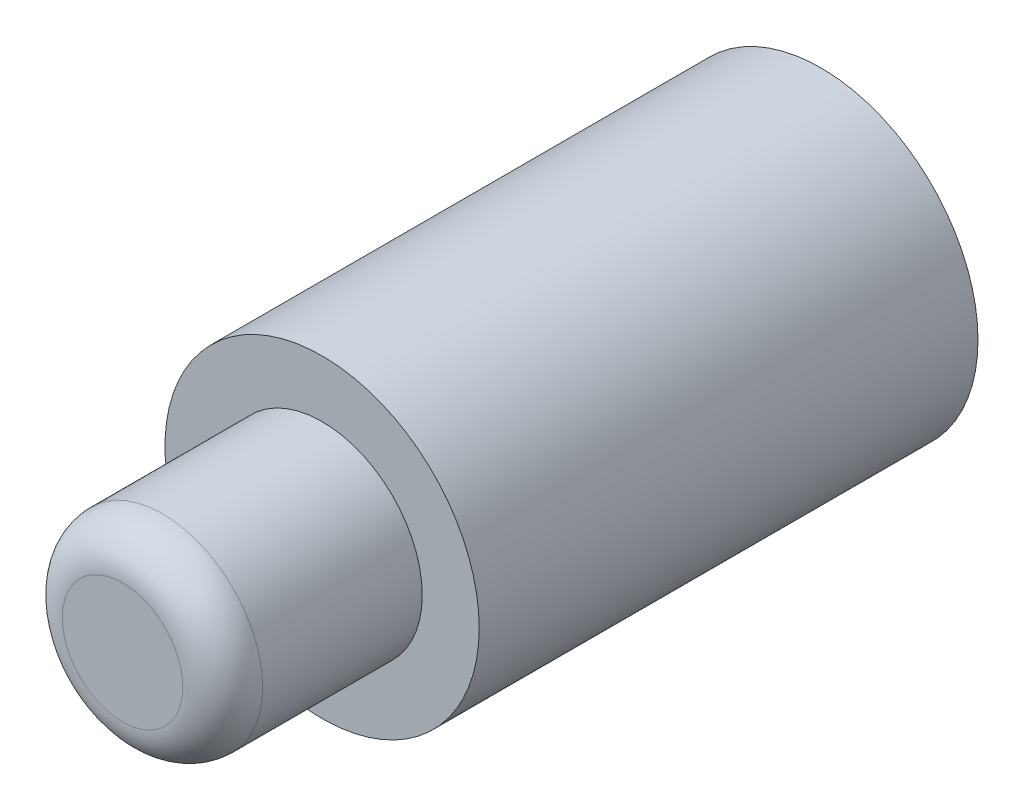
SolidWorks part; units mm, degrees
ref_plane "Front Plane" through (0, 0, 0) normal (0, 0, 1) x (1, 0, 0)
ref_plane "Top Plane" through (0, 0, 0) normal (0, 1, 0) x (1, 0, 0)
ref_plane "Right Plane" through (0, 0, 0) normal (1, 0, 0) x (0, 0, -1)
sketch "Sketch1" plane through (0, 0, 0) normal (0, 0, 1) x (1, 0, 0)
  circle A0 centre (0, 0) radius 2
  dimension "D1" = 4
extrude "Boss-Extrude1" add sketch "Sketch1" along normal blind 8.89
sketch "Sketch2" plane through (0, 0, 8.89) normal (0, 0, 1) x (1, 0, 0)
  circle A0 centre (0, 0) radius 1.275
  circle M2 centre (0, 0) radius 2
  dimension "D1" = 2.55
extrude "Cut-Extrude1" cut sketch "Sketch2" against normal blind 2.54 contours A0 M2
fillet "Fillet2" radius 0.508 1 edges at (1.275, 0, 8.89)
